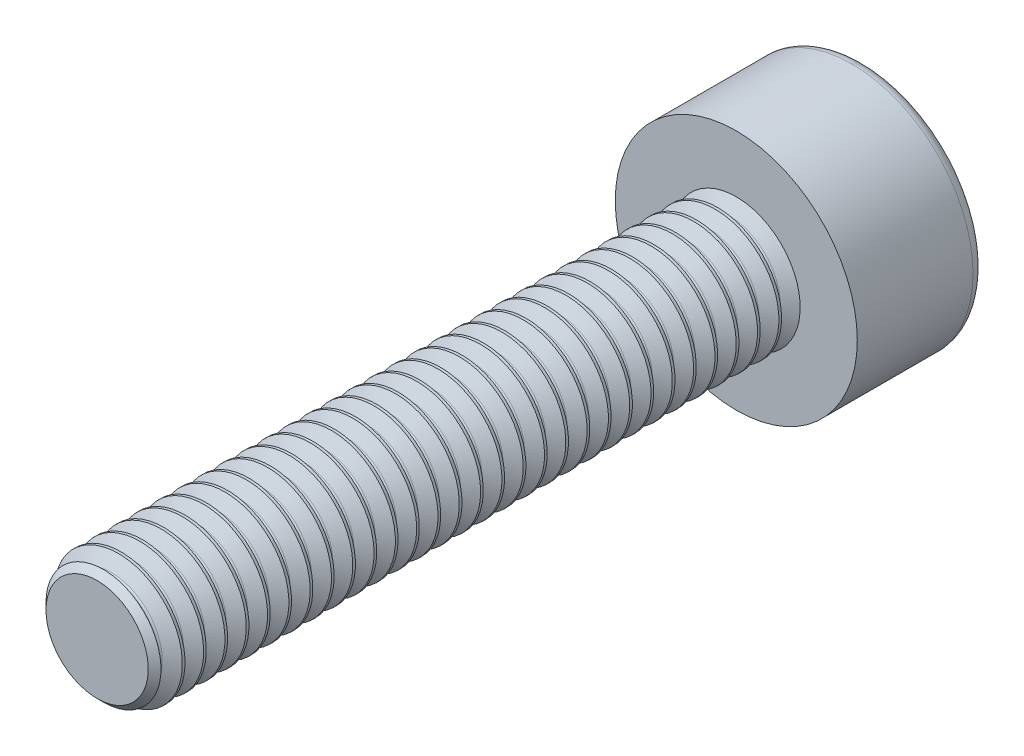
SolidWorks part; units mm, degrees
ref_plane "Front Plane" through (0, 0, 0) normal (0, 0, 1) x (1, 0, 0)
ref_plane "Top Plane" through (0, 0, 0) normal (0, 1, 0) x (1, 0, 0)
ref_plane "Right Plane" through (0, 0, 0) normal (1, 0, 0) x (0, 0, -1)
ref_plane "Plane1" through (0, 0, 0) normal (0, -1, 0) x (1, 0, 0)
sketch "Sketch1" plane through (0, 0, 0) normal (0, -1, 0) x (1, 0, 0)
  line L0 (1.2, 15) -> (0, 15)
  line L1 (0, 15) -> (0, -3)
  line L2 (0, -3) -> (2.84, -3)
  line L3 (2.84, -3) -> (2.84, 0)
  line L4 (2.84, 0) -> (1.5, 0)
  line L5 (1.5, 0) -> (1.2023, 0.1719)
  line L6 (1.2023, 0.2656) -> (1.5, 0.4375)
  line L7 (1.5, 0.4375) -> (1.5, 0.5)
  line L8 (1.5, 0.5) -> (1.2023, 0.6719)
  line L9 (1.2023, 0.7656) -> (1.5, 0.9375)
  line L10 (1.5, 0.9375) -> (1.5, 1)
  line L11 (1.5, 1) -> (1.2023, 1.1719)
  line L12 (1.2023, 1.2656) -> (1.5, 1.4375)
  line L13 (1.5, 1.4375) -> (1.5, 1.5)
  line L14 (1.5, 1.5) -> (1.2023, 1.6719)
  line L15 (1.2023, 1.7656) -> (1.5, 1.9375)
  line L16 (1.5, 1.9375) -> (1.5, 2)
  line L17 (1.5, 2) -> (1.2023, 2.1719)
  line L18 (1.2023, 2.2656) -> (1.5, 2.4375)
  line L19 (1.5, 2.4375) -> (1.5, 2.5)
  line L20 (1.5, 2.5) -> (1.2023, 2.6719)
  line L21 (1.2023, 2.7656) -> (1.5, 2.9375)
  line L22 (1.5, 2.9375) -> (1.5, 3)
  line L23 (1.5, 3) -> (1.2023, 3.1719)
  line L24 (1.2023, 3.2656) -> (1.5, 3.4375)
  line L25 (1.5, 3.4375) -> (1.5, 3.5)
  line L26 (1.5, 3.5) -> (1.2023, 3.6719)
  line L27 (1.2023, 3.7656) -> (1.5, 3.9375)
  line L28 (1.5, 3.9375) -> (1.5, 4)
  line L29 (1.5, 4) -> (1.2023, 4.1719)
  line L30 (1.2023, 4.2656) -> (1.5, 4.4375)
  line L31 (1.5, 4.4375) -> (1.5, 4.5)
  line L32 (1.5, 4.5) -> (1.2023, 4.6719)
  line L33 (1.2023, 4.7656) -> (1.5, 4.9375)
  line L34 (1.5, 4.9375) -> (1.5, 5)
  line L35 (1.5, 5) -> (1.2023, 5.1719)
  line L36 (1.2023, 5.2656) -> (1.5, 5.4375)
  line L37 (1.5, 5.4375) -> (1.5, 5.5)
  line L38 (1.5, 5.5) -> (1.2023, 5.6719)
  line L39 (1.2023, 5.7656) -> (1.5, 5.9375)
  line L40 (1.5, 5.9375) -> (1.5, 6)
  line L41 (1.5, 6) -> (1.2023, 6.1719)
  line L42 (1.2023, 6.2656) -> (1.5, 6.4375)
  line L43 (1.5, 6.4375) -> (1.5, 6.5)
  line L44 (1.5, 6.5) -> (1.2023, 6.6719)
  line L45 (1.2023, 6.7656) -> (1.5, 6.9375)
  line L46 (1.5, 6.9375) -> (1.5, 7)
  line L47 (1.5, 7) -> (1.2023, 7.1719)
  line L48 (1.2023, 7.2656) -> (1.5, 7.4375)
  line L49 (1.5, 7.4375) -> (1.5, 7.5)
  line L50 (1.5, 7.5) -> (1.2023, 7.6719)
  line L51 (1.2023, 7.7656) -> (1.5, 7.9375)
  line L52 (1.5, 7.9375) -> (1.5, 8)
  line L53 (1.5, 8) -> (1.2023, 8.1719)
  line L54 (1.2023, 8.2656) -> (1.5, 8.4375)
  line L55 (1.5, 8.4375) -> (1.5, 8.5)
  line L56 (1.5, 8.5) -> (1.2023, 8.6719)
  line L57 (1.2023, 8.7656) -> (1.5, 8.9375)
  line L58 (1.5, 8.9375) -> (1.5, 9)
  line L59 (1.5, 9) -> (1.2023, 9.1719)
  line L60 (1.2023, 9.2656) -> (1.5, 9.4375)
  line L61 (1.5, 9.4375) -> (1.5, 9.5)
  line L62 (1.5, 9.5) -> (1.2023, 9.6719)
  line L63 (1.2023, 9.7656) -> (1.5, 9.9375)
  line L64 (1.5, 9.9375) -> (1.5, 10)
  line L65 (1.5, 10) -> (1.2023, 10.1719)
  line L66 (1.2023, 10.2656) -> (1.5, 10.4375)
  line L67 (1.5, 10.4375) -> (1.5, 10.5)
  line L68 (1.5, 10.5) -> (1.2023, 10.6719)
  line L69 (1.2023, 10.7656) -> (1.5, 10.9375)
  line L70 (1.5, 10.9375) -> (1.5, 11)
  line L71 (1.5, 11) -> (1.2023, 11.1719)
  line L72 (1.2023, 11.2656) -> (1.5, 11.4375)
  line L73 (1.5, 11.4375) -> (1.5, 11.5)
  line L74 (1.5, 11.5) -> (1.2023, 11.6719)
  line L75 (1.2023, 11.7656) -> (1.5, 11.9375)
  line L76 (1.5, 11.9375) -> (1.5, 12)
  line L77 (1.5, 12) -> (1.2023, 12.1719)
  line L78 (1.2023, 12.2656) -> (1.5, 12.4375)
  line L79 (1.5, 12.4375) -> (1.5, 12.5)
  line L80 (1.5, 12.5) -> (1.2023, 12.6719)
  line L81 (1.2023, 12.7656) -> (1.5, 12.9375)
  line L82 (1.5, 12.9375) -> (1.5, 13)
  line L83 (1.5, 13) -> (1.2023, 13.1719)
  line L84 (1.2023, 13.2656) -> (1.5, 13.4375)
  line L85 (1.5, 13.4375) -> (1.5, 13.5)
  line L86 (1.5, 13.5) -> (1.2023, 13.6719)
  line L87 (1.2023, 13.7656) -> (1.5, 13.9375)
  line L88 (1.5, 13.9375) -> (1.5, 14)
  line L89 (1.5, 14) -> (1.2023, 14.1719)
  line L90 (1.2023, 14.2656) -> (1.5, 14.4375)
  line L91 (1.5, 14.4375) -> (1.5, 14.5)
  line L92 (1.5, 14.5) -> (1.2023, 14.6719)
  line L93 (1.2023, 14.7656) -> (1.3494, 14.8506)
  line L94 (1.3494, 14.8506) -> (1.2, 15)
  line L95 (0, 15) -> (0, -3) construction
  spline S0 degree 3 poles (1.1752, 0.2188) (1.1752, 0.2007) (1.1867, 0.1809) (1.2023, 0.1719) knots 0 0 0 0 1 1 1 1
  spline S1 degree 3 poles (1.2023, 0.2656) (1.1867, 0.2566) (1.1752, 0.2368) (1.1752, 0.2188) knots 0 0 0 0 1 1 1 1
  spline S2 degree 3 poles (1.2023, 0.6719) (1.1867, 0.6809) (1.1752, 0.7007) (1.1752, 0.7188) knots 0 0 0 0 1 1 1 1
  spline S3 degree 3 poles (1.1752, 0.7188) (1.1752, 0.7368) (1.1867, 0.7566) (1.2023, 0.7656) knots 0 0 0 0 1 1 1 1
  spline S4 degree 3 poles (1.2023, 1.1719) (1.1867, 1.1809) (1.1752, 1.2007) (1.1752, 1.2188) knots 0 0 0 0 1 1 1 1
  spline S5 degree 3 poles (1.1752, 1.2188) (1.1752, 1.2368) (1.1867, 1.2566) (1.2023, 1.2656) knots 0 0 0 0 1 1 1 1
  spline S6 degree 3 poles (1.2023, 1.6719) (1.1867, 1.6809) (1.1752, 1.7007) (1.1752, 1.7188) knots 0 0 0 0 1 1 1 1
  spline S7 degree 3 poles (1.1752, 1.7188) (1.1752, 1.7368) (1.1867, 1.7566) (1.2023, 1.7656) knots 0 0 0 0 1 1 1 1
  spline S8 degree 3 poles (1.2023, 2.1719) (1.1867, 2.1809) (1.1752, 2.2007) (1.1752, 2.2188) knots 0 0 0 0 1 1 1 1
  spline S9 degree 3 poles (1.1752, 2.2188) (1.1752, 2.2368) (1.1867, 2.2566) (1.2023, 2.2656) knots 0 0 0 0 1 1 1 1
  spline S10 degree 3 poles (1.2023, 2.6719) (1.1867, 2.6809) (1.1752, 2.7007) (1.1752, 2.7188) knots 0 0 0 0 1 1 1 1
  spline S11 degree 3 poles (1.1752, 2.7188) (1.1752, 2.7368) (1.1867, 2.7566) (1.2023, 2.7656) knots 0 0 0 0 1 1 1 1
  spline S12 degree 3 poles (1.2023, 3.1719) (1.1867, 3.1809) (1.1752, 3.2007) (1.1752, 3.2188) knots 0 0 0 0 1 1 1 1
  spline S13 degree 3 poles (1.1752, 3.2188) (1.1752, 3.2368) (1.1867, 3.2566) (1.2023, 3.2656) knots 0 0 0 0 1 1 1 1
  spline S14 degree 3 poles (1.2023, 3.6719) (1.1867, 3.6809) (1.1752, 3.7007) (1.1752, 3.7188) knots 0 0 0 0 1 1 1 1
  spline S15 degree 3 poles (1.1752, 3.7188) (1.1752, 3.7368) (1.1867, 3.7566) (1.2023, 3.7656) knots 0 0 0 0 1 1 1 1
  spline S16 degree 3 poles (1.2023, 4.1719) (1.1867, 4.1809) (1.1752, 4.2007) (1.1752, 4.2188) knots 0 0 0 0 1 1 1 1
  spline S17 degree 3 poles (1.1752, 4.2188) (1.1752, 4.2368) (1.1867, 4.2566) (1.2023, 4.2656) knots 0 0 0 0 1 1 1 1
  spline S18 degree 3 poles (1.2023, 4.6719) (1.1867, 4.6809) (1.1752, 4.7007) (1.1752, 4.7188) knots 0 0 0 0 1 1 1 1
  spline S19 degree 3 poles (1.1752, 4.7188) (1.1752, 4.7368) (1.1867, 4.7566) (1.2023, 4.7656) knots 0 0 0 0 1 1 1 1
  spline S20 degree 3 poles (1.2023, 5.1719) (1.1867, 5.1809) (1.1752, 5.2007) (1.1752, 5.2188) knots 0 0 0 0 1 1 1 1
  spline S21 degree 3 poles (1.1752, 5.2188) (1.1752, 5.2368) (1.1867, 5.2566) (1.2023, 5.2656) knots 0 0 0 0 1 1 1 1
  spline S22 degree 3 poles (1.2023, 5.6719) (1.1867, 5.6809) (1.1752, 5.7007) (1.1752, 5.7188) knots 0 0 0 0 1 1 1 1
  spline S23 degree 3 poles (1.1752, 5.7188) (1.1752, 5.7368) (1.1867, 5.7566) (1.2023, 5.7656) knots 0 0 0 0 1 1 1 1
  spline S24 degree 3 poles (1.2023, 6.1719) (1.1867, 6.1809) (1.1752, 6.2007) (1.1752, 6.2188) knots 0 0 0 0 1 1 1 1
  spline S25 degree 3 poles (1.1752, 6.2188) (1.1752, 6.2368) (1.1867, 6.2566) (1.2023, 6.2656) knots 0 0 0 0 1 1 1 1
  spline S26 degree 3 poles (1.2023, 6.6719) (1.1867, 6.6809) (1.1752, 6.7007) (1.1752, 6.7188) knots 0 0 0 0 1 1 1 1
  spline S27 degree 3 poles (1.1752, 6.7188) (1.1752, 6.7368) (1.1867, 6.7566) (1.2023, 6.7656) knots 0 0 0 0 1 1 1 1
  spline S28 degree 3 poles (1.2023, 7.1719) (1.1867, 7.1809) (1.1752, 7.2007) (1.1752, 7.2188) knots 0 0 0 0 1 1 1 1
  spline S29 degree 3 poles (1.1752, 7.2188) (1.1752, 7.2368) (1.1867, 7.2566) (1.2023, 7.2656) knots 0 0 0 0 1 1 1 1
  spline S30 degree 3 poles (1.2023, 7.6719) (1.1867, 7.6809) (1.1752, 7.7007) (1.1752, 7.7188) knots 0 0 0 0 1 1 1 1
  spline S31 degree 3 poles (1.1752, 7.7188) (1.1752, 7.7368) (1.1867, 7.7566) (1.2023, 7.7656) knots 0 0 0 0 1 1 1 1
  spline S32 degree 3 poles (1.2023, 8.1719) (1.1867, 8.1809) (1.1752, 8.2007) (1.1752, 8.2188) knots 0 0 0 0 1 1 1 1
  spline S33 degree 3 poles (1.1752, 8.2188) (1.1752, 8.2368) (1.1867, 8.2566) (1.2023, 8.2656) knots 0 0 0 0 1 1 1 1
  spline S34 degree 3 poles (1.2023, 8.6719) (1.1867, 8.6809) (1.1752, 8.7007) (1.1752, 8.7188) knots 0 0 0 0 1 1 1 1
  spline S35 degree 3 poles (1.1752, 8.7188) (1.1752, 8.7368) (1.1867, 8.7566) (1.2023, 8.7656) knots 0 0 0 0 1 1 1 1
  spline S36 degree 3 poles (1.2023, 9.1719) (1.1867, 9.1809) (1.1752, 9.2007) (1.1752, 9.2188) knots 0 0 0 0 1 1 1 1
  spline S37 degree 3 poles (1.1752, 9.2188) (1.1752, 9.2368) (1.1867, 9.2566) (1.2023, 9.2656) knots 0 0 0 0 1 1 1 1
  spline S38 degree 3 poles (1.2023, 9.6719) (1.1867, 9.6809) (1.1752, 9.7007) (1.1752, 9.7188) knots 0 0 0 0 1 1 1 1
  spline S39 degree 3 poles (1.1752, 9.7188) (1.1752, 9.7368) (1.1867, 9.7566) (1.2023, 9.7656) knots 0 0 0 0 1 1 1 1
  spline S40 degree 3 poles (1.2023, 10.1719) (1.1867, 10.1809) (1.1752, 10.2007) (1.1752, 10.2188) knots 0 0 0 0 1 1 1 1
  spline S41 degree 3 poles (1.1752, 10.2188) (1.1752, 10.2368) (1.1867, 10.2566) (1.2023, 10.2656) knots 0 0 0 0 1 1 1 1
  spline S42 degree 3 poles (1.2023, 10.6719) (1.1867, 10.6809) (1.1752, 10.7007) (1.1752, 10.7188) knots 0 0 0 0 1 1 1 1
  spline S43 degree 3 poles (1.1752, 10.7188) (1.1752, 10.7368) (1.1867, 10.7566) (1.2023, 10.7656) knots 0 0 0 0 1 1 1 1
  spline S44 degree 3 poles (1.2023, 11.1719) (1.1867, 11.1809) (1.1752, 11.2007) (1.1752, 11.2188) knots 0 0 0 0 1 1 1 1
  spline S45 degree 3 poles (1.1752, 11.2188) (1.1752, 11.2368) (1.1867, 11.2566) (1.2023, 11.2656) knots 0 0 0 0 1 1 1 1
  spline S46 degree 3 poles (1.2023, 11.6719) (1.1867, 11.6809) (1.1752, 11.7007) (1.1752, 11.7188) knots 0 0 0 0 1 1 1 1
  spline S47 degree 3 poles (1.1752, 11.7188) (1.1752, 11.7368) (1.1867, 11.7566) (1.2023, 11.7656) knots 0 0 0 0 1 1 1 1
  spline S48 degree 3 poles (1.2023, 12.1719) (1.1867, 12.1809) (1.1752, 12.2007) (1.1752, 12.2188) knots 0 0 0 0 1 1 1 1
  spline S49 degree 3 poles (1.1752, 12.2188) (1.1752, 12.2368) (1.1867, 12.2566) (1.2023, 12.2656) knots 0 0 0 0 1 1 1 1
  spline S50 degree 3 poles (1.2023, 12.6719) (1.1867, 12.6809) (1.1752, 12.7007) (1.1752, 12.7188) knots 0 0 0 0 1 1 1 1
  spline S51 degree 3 poles (1.1752, 12.7188) (1.1752, 12.7368) (1.1867, 12.7566) (1.2023, 12.7656) knots 0 0 0 0 1 1 1 1
  spline S52 degree 3 poles (1.2023, 13.1719) (1.1867, 13.1809) (1.1752, 13.2007) (1.1752, 13.2188) knots 0 0 0 0 1 1 1 1
  spline S53 degree 3 poles (1.1752, 13.2188) (1.1752, 13.2368) (1.1867, 13.2566) (1.2023, 13.2656) knots 0 0 0 0 1 1 1 1
  spline S54 degree 3 poles (1.2023, 13.6719) (1.1867, 13.6809) (1.1752, 13.7007) (1.1752, 13.7188) knots 0 0 0 0 1 1 1 1
  spline S55 degree 3 poles (1.1752, 13.7188) (1.1752, 13.7368) (1.1867, 13.7566) (1.2023, 13.7656) knots 0 0 0 0 1 1 1 1
  spline S56 degree 3 poles (1.2023, 14.1719) (1.1867, 14.1809) (1.1752, 14.2007) (1.1752, 14.2188) knots 0 0 0 0 1 1 1 1
  spline S57 degree 3 poles (1.1752, 14.2188) (1.1752, 14.2368) (1.1867, 14.2566) (1.2023, 14.2656) knots 0 0 0 0 1 1 1 1
  spline S58 degree 3 poles (1.1752, 14.7187) (1.1752, 14.7007) (1.1867, 14.6809) (1.2023, 14.6719) knots 0 0 0 0 1 1 1 1
  spline S59 degree 3 poles (1.2023, 14.7656) (1.1867, 14.7566) (1.1752, 14.7368) (1.1752, 14.7187) knots 0 0 0 0 1 1 1 1
revolve "Revolve1" add sketch "Sketch1" angle 360 about L95
sketch "Sketch2" plane through (0, 0, -3) normal (0, 0, -1) x (-1, 0, 0)
  line L0 (-1.4434, 0) -> (-0.7217, -1.25)
  line L1 (-0.7217, -1.25) -> (0.7217, -1.25)
  line L2 (0.7217, -1.25) -> (1.4434, 0)
  line L3 (1.4434, 0) -> (0.7217, 1.25)
  line L4 (0.7217, 1.25) -> (-0.7217, 1.25)
  line L5 (-0.7217, 1.25) -> (-1.4434, 0)
extrude "Cut-Extrude1" cut sketch "Sketch2" against normal blind 1.5
fillet "Fillet1" radius 0.284 1 edges at (-2.84, 0, -3)
